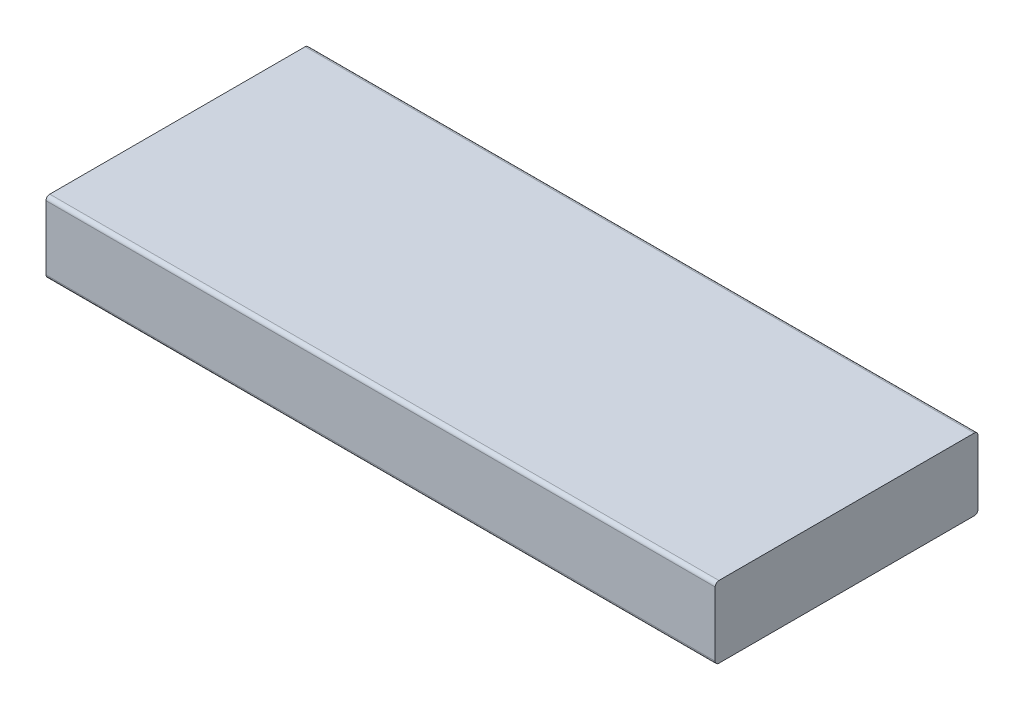
SolidWorks part; units mm, degrees
ref_plane "Front Plane" through (0, 0, 0) normal (0, 0, 1) x (1, 0, 0)
ref_plane "Top Plane" through (0, 0, 0) normal (0, 1, 0) x (1, 0, 0)
ref_plane "Right Plane" through (0, 0, 0) normal (1, 0, 0) x (0, 0, -1)
sketch "Sketch1" plane through (0, 0, 0) normal (1, 0, 0) x (0, 0, -1)
  line L1 (-69.85, -19.05) -> (69.85, -19.05)
  line L2 (-69.85, -19.05) -> (-69.85, 19.05)
  line L3 (-69.85, 19.05) -> (69.85, 19.05)
  line L4 (69.85, -19.05) -> (69.85, 19.05)
  line L5 (-69.85, -19.05) -> (69.85, 19.05) construction
  line L6 (-69.85, 19.05) -> (69.85, -19.05) construction
  point P0 (0, 0)
  dimension "D1" = 38.1
  dimension "D2" = 139.7
extrude "Boss-Extrude1" add sketch "Sketch1" along normal blind 355.6
fillet "Fillet1" radius 2 4 edges at (177.8, 19.05, 69.85) (177.8, 19.05, -69.85) (177.8, -19.05, -69.85) (177.8, -19.05, 69.85)
other "2x4<1>"
ref_plane "Plane1" through (177.8, 0, 0) normal (1, 0, 0) x (0, 0, -1)
sketch "Sketch3" plane through (0, 19.05, 0) normal (0, 1, 0) x (1, 0, 0)
  line L0 (177.8, -69.85) -> (177.8, 69.85) construction
  line L1 (355.6, -69.85) -> (0, -69.85) construction
  line L2 (0, 69.85) -> (355.6, 69.85) construction
  point P10 (177.8, 0)
